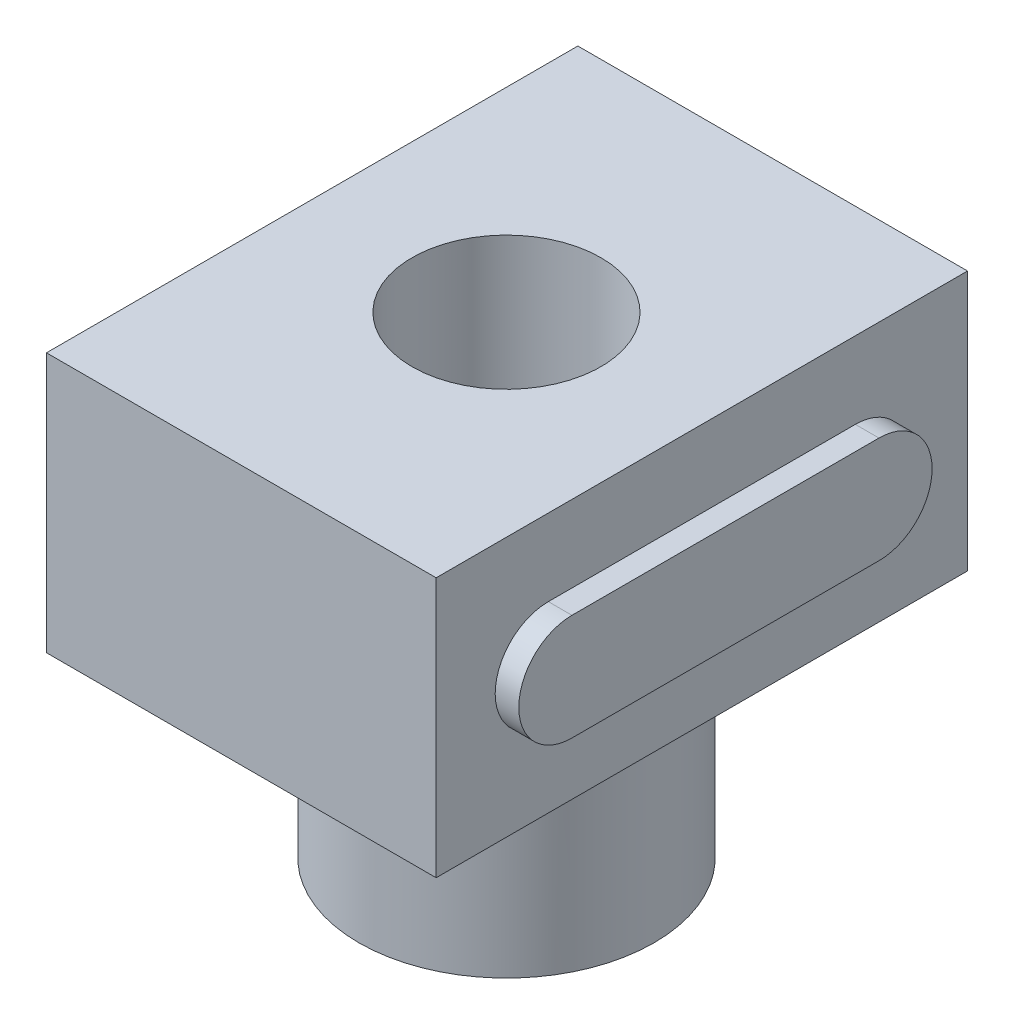
SolidWorks part; units mm, degrees
ref_plane "Plano frontal" through (0, 0, 0) normal (0, 0, 1) x (1, 0, 0)
ref_plane "Plano superior" through (0, 0, 0) normal (0, 1, 0) x (1, 0, 0)
ref_plane "Plano direito" through (0, 0, 0) normal (1, 0, 0) x (0, 0, -1)
sketch "Esboço1" plane through (0, 0, 0) normal (0, 1, 0) x (1, 0, 0)
  circle A0 centre (0, 0) radius 12.5
  dimension "D1" = 25
extrude "Ressalto-extrusão1" add sketch "Esboço1" along normal blind 30
sketch "Esboço2" plane through (0, 30, 0) normal (0, 1, 0) x (1, 0, 0)
  circle A0 centre (0, 0) radius 8
extrude "Corte-extrusão1" cut sketch "Esboço2" against normal blind 15
sketch "Esboço3" plane through (0, 0, 0) normal (0, -1, 0) x (1, 0, 0)
  line L1 (-1.5, 2.5) -> (1.5, 2.5)
  line L2 (-1.5, 2.5) -> (-1.5, -2.5)
  line L3 (-1.5, -2.5) -> (1.5, -2.5)
  line L4 (1.5, 2.5) -> (1.5, -2.5)
  circle A0 centre (0, 0) radius 12.5 construction
  dimension "D1" = 3
  dimension "D2" = 5
  dimension "D3" = 1.5
  dimension "D4" = 2.5
extrude "Corte-extrusão2" cut sketch "Esboço3" against normal blind 6.5
sketch "Esboço4" plane through (0, 30, 0) normal (0, 1, 0) x (1, 0, 0)
  circle A0 centre (0, 0) radius 8
extrude "Corte-extrusão3" cut sketch "Esboço4" against normal through all
sketch "Esboço5" plane through (0, 30, 0) normal (0, 1, 0) x (1, 0, 0)
  line L1 (-12.5, -12.5) -> (12.5, -12.5)
  line L2 (-12.5, -12.5) -> (-12.5, 12.5)
  line L3 (-12.5, 12.5) -> (12.5, 12.5)
  line L4 (12.5, -12.5) -> (12.5, 12.5)
  line L5 (-12.5, -12.5) -> (12.5, 12.5) construction
  line L6 (-12.5, 12.5) -> (12.5, -12.5) construction
  point P0 (0, 0)
  dimension "D1" = 25
  dimension "D2" = 25
extrude "Ressalto-extrusão2" add sketch "Esboço5" against normal blind 12
sketch "Esboço6" plane through (0, 30, 0) normal (0, 1, 0) x (1, 0, 0)
  line L1 (-12.5, -12.5) -> (12.5, -12.5)
  line L2 (-12.5, -12.5) -> (-12.5, 12.5)
  line L3 (-12.5, 12.5) -> (12.5, 12.5)
  line L4 (12.5, -12.5) -> (12.5, 12.5)
  line L5 (-12.5, -12.5) -> (12.5, 12.5) construction
  line L6 (-12.5, 12.5) -> (12.5, -12.5) construction
  point P0 (0, 0)
extrude "Ressalto-extrusão3" add sketch "Esboço6" along normal blind 10
sketch "Esboço7" plane through (0, 18, 0) normal (0, -1, 0) x (1, 0, 0)
  circle A0 centre (0, 0) radius 8
extrude "Corte-extrusão4" cut sketch "Esboço7" against normal through all
sketch "Esboço8" plane through (12.5, 0, 0) normal (1, 0, 0) x (0, 0, -1)
  line L1 (-22.4553, 40) -> (22.5447, 40)
  line L2 (-22.4553, 40) -> (-22.4553, 18)
  line L3 (-22.4553, 18) -> (22.5447, 18)
  line L4 (22.5447, 40) -> (22.5447, 18)
  line L5 (-22.4553, 40) -> (22.5447, 18) construction
  line L6 (-22.4553, 18) -> (22.5447, 40) construction
  point P0 (0.0447, 29)
  dimension "D1" = 45
extrude "Ressalto-extrusão4" add sketch "Esboço8" against normal blind 25
sketch "Esboço9" plane through (-12.5, 0, 0) normal (-1, 0, 0) x (0, 0, 1)
  line L1 (22.5447, 40) -> (-22.5447, 40)
  line L2 (22.5447, 40) -> (22.5447, 18)
  line L3 (22.5447, 18) -> (-22.5447, 18)
  line L4 (-22.5447, 40) -> (-22.5447, 18)
  line L5 (22.5447, 40) -> (-22.5447, 18) construction
  line L6 (22.5447, 18) -> (-22.5447, 40) construction
  point P0 (0, 29)
extrude "Ressalto-extrusão5" add sketch "Esboço9" along normal blind 4
sketch "Esboço10" plane through (12.5, 0, 0) normal (1, 0, 0) x (0, 0, -1)
  line L1 (-22.5447, 40) -> (22.5447, 40)
  line L2 (-22.5447, 40) -> (-22.5447, 18)
  line L3 (-22.5447, 18) -> (22.5447, 18)
  line L4 (22.5447, 40) -> (22.5447, 18)
  line L5 (-22.5447, 40) -> (22.5447, 18) construction
  line L6 (-22.5447, 18) -> (22.5447, 40) construction
  point P0 (0, 29)
extrude "Ressalto-extrusão6" add sketch "Esboço10" along normal blind 4
sketch "Esboço11" plane through (0, 40, 0) normal (0, 1, 0) x (1, 0, 0)
  line L0 (16.5, 22.5447) -> (16.5, -22.5447) construction
  line L1 (-16.5, 22.5447) -> (16.5, 22.5447)
  line L2 (-16.5, 22.5447) -> (-16.5, -22.4553)
  line L3 (-16.5, -22.4553) -> (16.5, -22.4553)
  line L4 (16.5, 22.5447) -> (16.5, -22.4553)
extrude "Ressalto-extrusão7" add sketch "Esboço11" against normal blind 22
sketch "Esboço12" plane through (0, 40, 0) normal (0, 1, 0) x (1, 0, 0)
  line L1 (-12.5, -22.4553) -> (-16.5, -22.4553)
  line L2 (-12.5, -22.4553) -> (-12.5, -22.5447)
  line L3 (-12.5, -22.5447) -> (-16.5, -22.5447)
  line L4 (-16.5, -22.4553) -> (-16.5, -22.5447)
  line L5 (12.5, -22.4553) -> (16.5, -22.4553)
  line L6 (12.5, -22.4553) -> (12.5, -22.5447)
  line L7 (12.5, -22.5447) -> (16.5, -22.5447)
  line L8 (16.5, -22.4553) -> (16.5, -22.5447)
extrude "Corte-extrusão5" cut sketch "Esboço12" against normal through all
sketch "Esboço13" plane through (-16.5, 0, 0) normal (-1, 0, 0) x (0, 0, 1)
  line L1 (-13.0447, 33.5) -> (12.9553, 33.5)
  line L3 (-13.0447, 24.5) -> (12.9553, 24.5)
  line L5 (22.4553, 40) -> (-22.5447, 40) construction
  arc A0 (-13.0447, 33.5) -> (-13.0447, 24.5) centre (-13.0447, 29) ccw
  arc A1 (12.9553, 24.5) -> (12.9553, 33.5) centre (12.9553, 29) ccw
  dimension "D3" = 9
  dimension "D6" = 9
  dimension "D5" = 4.5
  dimension "D8" = 6.5
extrude "Ressalto-extrusão8" add sketch "Esboço13" along normal blind 2
sketch "Esboço14" plane through (16.5, 0, 0) normal (1, 0, 0) x (0, 0, -1)
  line L0 (22.5447, 40) -> (-22.4553, 40) construction
  line L1 (-12.9553, 24.5) -> (13.0447, 24.5)
  line L3 (-12.9553, 33.5) -> (13.0447, 33.5)
  line L5 (-17.4553, 24.5) -> (-15.176, 25.0861) construction
  line L6 (-17.4553, 33.5) -> (-15.176, 32.9139) construction
  line L9 (15.2653, 32.9139) -> (17.5447, 33.5) construction
  arc A0 (-12.9553, 33.5) -> (-12.9553, 24.5) centre (-12.9553, 29) ccw
  arc A1 (13.0447, 24.5) -> (13.0447, 33.5) centre (13.0447, 29) ccw
  point P0 (0.0447, 29)
  point P14 (0, 0)
  dimension "D5" = 9
  dimension "D8" = 9
  dimension "D1" = 35
  dimension "D3" = 6.5
  dimension "D6" = 4.5
  dimension "D10" = 4.5
extrude "Ressalto-extrusão9" add sketch "Esboço14" along normal blind 2
sketch "Esboço15" plane through (0, 18, 0) normal (0, -1, 0) x (1, 0, 0)
  circle A0 centre (0, 0) radius 8
extrude "Corte-extrusão6" cut sketch "Esboço15" against normal through all
